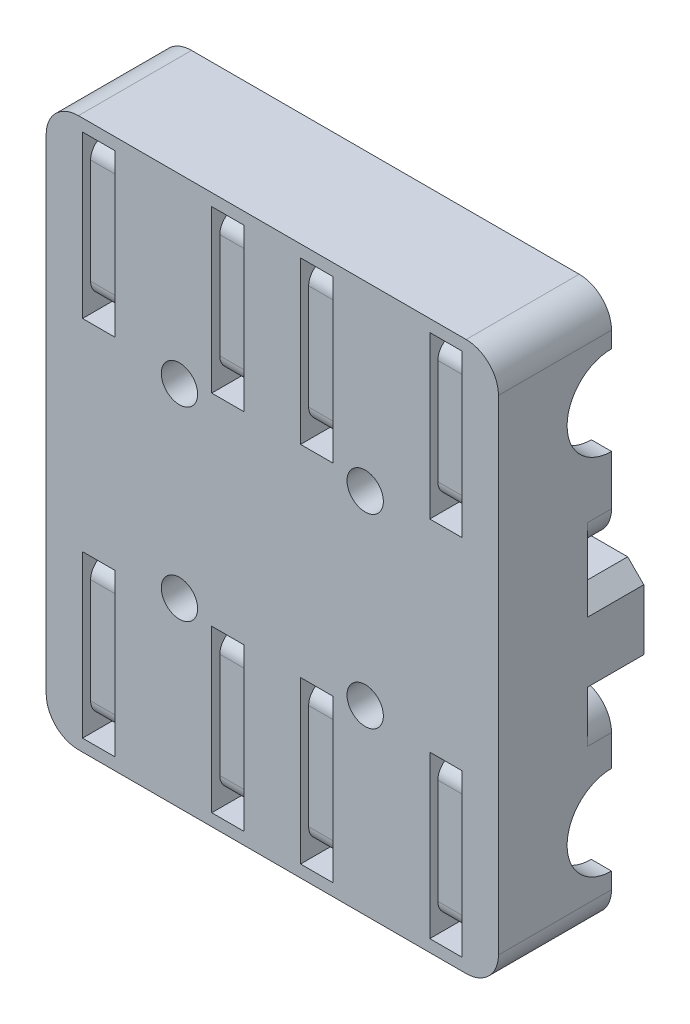
SolidWorks part; units mm, degrees
material "ABS"
ref_plane "Front Plane" through (0, 0, 0) normal (0, 0, 1) x (1, 0, 0)
ref_plane "Top Plane" through (0, 0, 0) normal (0, 1, 0) x (1, 0, 0)
ref_plane "Right Plane" through (0, 0, 0) normal (1, 0, 0) x (0, 0, -1)
sketch "Sketch1" plane through (0, 0, 0) normal (0, 0, 1) x (1, 0, 0)
  line L1 (0, 0) -> (56, 0)
  line L2 (0, 0) -> (0, 68)
  line L3 (0, 68) -> (56, 68)
  line L4 (56, 0) -> (56, 68)
  dimension "D1" = 68
  dimension "D2" = 56
extrude "Boss-Extrude1" add sketch "Sketch1" along normal blind 18
sketch "Sketch2" plane through (0, 0, 18) normal (0, 0, 1) x (1, 0, 0)
  line L0 (0, 34) -> (56, 34) construction
  line L1 (4, 68) -> (52, 68)
  line L2 (0, 64) -> (0, 4)
  line L3 (4, 0) -> (52, 0)
  line L4 (56, 64) -> (56, 4)
  line L5 (4.5, 47.25) -> (0, 47.25) construction
  line L6 (4.5, 48) -> (8.5, 48)
  line L7 (39.5, 45.5) -> (16.5, 45.5) construction
  line L8 (28, 45.5) -> (28, 68) construction
  line L9 (4.5, 48) -> (4.5, 46.5)
  line L10 (4.5, 46.5) -> (8.5, 46.5)
  line L11 (8.5, 48) -> (8.5, 46.5)
  line L12 (0, 68) -> (0, 0) construction
  line L13 (8.5, 47.25) -> (20.5, 47.25) construction
  line L14 (24.5, 47.25) -> (31.5, 47.25) construction
  line L15 (20.5, 48) -> (24.5, 48)
  line L16 (20.5, 48) -> (20.5, 46.5)
  line L17 (20.5, 46.5) -> (24.5, 46.5)
  line L18 (24.5, 48) -> (24.5, 46.5)
  line L19 (35.5, 47.25) -> (47.5, 47.25) construction
  line L20 (31.5, 48) -> (35.5, 48)
  line L21 (31.5, 48) -> (31.5, 46.5)
  line L22 (31.5, 46.5) -> (35.5, 46.5)
  line L23 (35.5, 48) -> (35.5, 46.5)
  line L24 (51.5, 47.25) -> (56, 47.25) construction
  line L25 (47.5, 48) -> (51.5, 48)
  line L26 (47.5, 48) -> (47.5, 46.5)
  line L27 (47.5, 46.5) -> (51.5, 46.5)
  line L28 (51.5, 48) -> (51.5, 46.5)
  line L29 (0, 56.5) -> (56, 56.5) construction
  line L30 (47.5, 65) -> (51.5, 65)
  line L31 (51.5, 65) -> (51.5, 66.5)
  line L32 (47.5, 66.5) -> (51.5, 66.5)
  line L33 (47.5, 65) -> (47.5, 66.5)
  line L34 (35.5, 65) -> (35.5, 66.5)
  line L35 (31.5, 65) -> (35.5, 65)
  line L36 (31.5, 66.5) -> (35.5, 66.5)
  line L37 (31.5, 65) -> (31.5, 66.5)
  line L38 (20.5, 65) -> (24.5, 65)
  line L39 (20.5, 65) -> (20.5, 66.5)
  line L40 (24.5, 65) -> (24.5, 66.5)
  line L41 (20.5, 66.5) -> (24.5, 66.5)
  line L42 (8.5, 65) -> (8.5, 66.5)
  line L43 (4.5, 65) -> (8.5, 65)
  line L44 (4.5, 66.5) -> (8.5, 66.5)
  line L45 (4.5, 65) -> (4.5, 66.5)
  line L46 (8.5, 20) -> (8.5, 21.5)
  line L47 (4.5, 21.5) -> (8.5, 21.5)
  line L48 (4.5, 20) -> (4.5, 21.5)
  line L49 (4.5, 20) -> (8.5, 20)
  line L50 (24.5, 20) -> (24.5, 21.5)
  line L51 (20.5, 21.5) -> (24.5, 21.5)
  line L52 (20.5, 20) -> (20.5, 21.5)
  line L53 (20.5, 20) -> (24.5, 20)
  line L54 (35.5, 20) -> (35.5, 21.5)
  line L55 (31.5, 21.5) -> (35.5, 21.5)
  line L56 (31.5, 20) -> (31.5, 21.5)
  line L57 (31.5, 20) -> (35.5, 20)
  line L58 (51.5, 20) -> (51.5, 21.5)
  line L59 (47.5, 21.5) -> (51.5, 21.5)
  line L60 (47.5, 20) -> (47.5, 21.5)
  line L61 (47.5, 20) -> (51.5, 20)
  line L62 (47.5, 3) -> (47.5, 1.5)
  line L63 (47.5, 1.5) -> (51.5, 1.5)
  line L64 (51.5, 3) -> (51.5, 1.5)
  line L65 (47.5, 3) -> (51.5, 3)
  line L66 (31.5, 3) -> (31.5, 1.5)
  line L67 (31.5, 1.5) -> (35.5, 1.5)
  line L68 (31.5, 3) -> (35.5, 3)
  line L69 (35.5, 3) -> (35.5, 1.5)
  line L70 (20.5, 1.5) -> (24.5, 1.5)
  line L71 (24.5, 3) -> (24.5, 1.5)
  line L72 (20.5, 3) -> (20.5, 1.5)
  line L73 (20.5, 3) -> (24.5, 3)
  line L74 (4.5, 3) -> (4.5, 1.5)
  line L75 (4.5, 1.5) -> (8.5, 1.5)
  line L76 (4.5, 3) -> (8.5, 3)
  line L77 (8.5, 3) -> (8.5, 1.5)
  line L78 (16.5, 45.5) -> (16.5, 22.5) construction
  line L79 (39.5, 45.5) -> (39.5, 22.5) construction
  arc A0 (56, 4) -> (52, 0) centre (52, 4) cw
  arc A1 (4, 0) -> (0, 4) centre (4, 4) cw
  arc A2 (56, 64) -> (52, 68) centre (52, 64) ccw
  arc A3 (4, 68) -> (0, 64) centre (4, 64) ccw
  circle A4 centre (16.5, 22.5) radius 2.25
  circle A5 centre (16.5, 45.5) radius 2.25
  circle A6 centre (39.5, 45.5) radius 2.25
  circle A7 centre (39.5, 22.5) radius 2.25
  point P8 (56, 0)
  point P15 (0, 68)
  point P106 (39.5, 22.5)
  point P107 (39.5, 19.4757)
  point P108 (16.5, 22.5)
  point P109 (16.5, 22)
  line M29 (0, 68) -> (0, 0)
  line M30 (0, 0) -> (56, 0)
  line M31 (56, 0) -> (56, 68)
  line M32 (56, 68) -> (0, 68)
  dimension "D1" = 4
  dimension "D2" = 4.5
  dimension "D3" = 23
  dimension "D4" = 22.5
  dimension "D5" = 1.5
  dimension "D6" = 4
  dimension "D7" = 4.5
  dimension "D8" = 12
  dimension "D9" = 20.75
  dimension "D10" = 9.25
  dimension "D11" = 23
  dimension "D12" = 23
extrude "Cut-Extrude1" cut sketch "Sketch2" against normal through all contours L45 L43 L42 L44 | L41 L39 L38 L40 | L37 L35 L34 L36 | L28 L25 L26 L27 | A6 | L23 L20 L21 L22 | L18 L15 L16 L17 | A5 | L11 L6 L9 L10 | L48 L49 L46 L47 | A4 | L52 L53 L50 L51 | A7 | L73 L72 L70 L71 | A1 M30 M29 | A0 M31 M30 | A3 M32 M29 | A2 M31 M32 | L30 L31 L32 L33 | L57 L54 L55 L56 | L59 L58 L61 L60 | L65 L64 L63 L62 | L67 L69 L68 L66 | L75 L77 L76 L74
sketch "Sketch3" plane through (0, 0, 18) normal (0, 0, 1) x (1, 0, 0)
  line L0 (56, 34) -> (0, 34) construction
  line L1 (4.5, 65) -> (8.5, 65)
  line L2 (4.5, 65) -> (4.5, 48)
  line L3 (4.5, 48) -> (8.5, 48)
  line L4 (8.5, 65) -> (8.5, 48)
  line L5 (20.5, 65) -> (24.5, 65)
  line L6 (20.5, 65) -> (20.5, 48)
  line L7 (20.5, 48) -> (24.5, 48)
  line L8 (24.5, 65) -> (24.5, 48)
  line L9 (31.5, 65) -> (35.5, 65)
  line L10 (31.5, 65) -> (31.5, 48)
  line L11 (31.5, 48) -> (35.5, 48)
  line L12 (35.5, 65) -> (35.5, 48)
  line L13 (47.5, 65) -> (51.5, 65)
  line L14 (47.5, 65) -> (47.5, 48)
  line L15 (47.5, 48) -> (51.5, 48)
  line L16 (51.5, 65) -> (51.5, 48)
  line L17 (56, 4) -> (56, 64) construction
  line L18 (0, 64) -> (0, 4) construction
  line L19 (51.5, 3) -> (51.5, 20)
  line L20 (47.5, 20) -> (51.5, 20)
  line L21 (47.5, 3) -> (47.5, 20)
  line L22 (47.5, 3) -> (51.5, 3)
  line L23 (35.5, 3) -> (35.5, 20)
  line L24 (31.5, 20) -> (35.5, 20)
  line L25 (31.5, 3) -> (31.5, 20)
  line L26 (31.5, 3) -> (35.5, 3)
  line L27 (24.5, 3) -> (24.5, 20)
  line L28 (20.5, 20) -> (24.5, 20)
  line L29 (20.5, 3) -> (20.5, 20)
  line L30 (20.5, 3) -> (24.5, 3)
  line L31 (8.5, 3) -> (8.5, 20)
  line L32 (4.5, 20) -> (8.5, 20)
  line L33 (4.5, 3) -> (4.5, 20)
  line L34 (4.5, 3) -> (8.5, 3)
extrude "Cut-Extrude2" cut sketch "Sketch3" against normal blind 1
ref_plane "Plane2" through (53.5, 0, 0) normal (1, 0, 0) x (0, 0, -1)
sketch "Sketch5" plane through (53.5, 0, 0) normal (1, 0, 0) x (0, 0, -1)
  line L1 (0, 0) -> (-18, 0) construction
  line L2 (0, 4) -> (0, 64) construction
  circle A0 centre (-4, 11.5) radius 7.5
  point P2 (-1.2356, 11.5)
  point P6 (0, 0)
  dimension "D1" = 15
  dimension "D2" = 11.5
  dimension "D3" = 4
extrude "Cut-Extrude3" cut sketch "Sketch5" against normal blind 24.5 contours A0
ref_plane "Plane3" through (28, 0, 0) normal (1, 0, 0) x (0, 0, -1)
ref_plane "Plane4" through (0, 34, 0) normal (0, -1, 0) x (-1, 0, 0)
mirror "Mirror1" about plane through (28, 0, 0) normal (1, 0, 0) of "Cut-Extrude3"
sketch "Sketch7" plane through (56, 0, 0) normal (1, 0, 0) x (0, 0, -1)
  line L1 (0, 0) -> (-18, 0) construction
  line L2 (0, 4) -> (0, 64) construction
  circle A0 centre (-4, 11.5) radius 5.5
  point P2 (-1.5987, 11.5)
  point P6 (0, 0)
  dimension "D1" = 11
  dimension "D2" = 11.5
  dimension "D3" = 4
extrude "Cut-Extrude4" cut sketch "Sketch7" against normal through all
mirror "Mirror3" about plane through (0, 34, 0) normal (0, -1, 0) of "Cut-Extrude3", "Mirror1", "Cut-Extrude4"
fillet "Fillet1" radius 2 16 edges at (49.5, 3, 17) (33.5, 3, 17) (22.5, 3, 17) (6.5, 3, 17) (6.5, 20, 17) (22.5, 20, 17) (33.5, 20, 17) (49.5, 20, 17) (6.5, 48, 17) (6.5, 65, 17) (22.5, 65, 17) (22.5, 48, 17) (33.5, 48, 17) (33.5, 65, 17) (49.5, 65, 17) (49.5, 48, 17)
sketch "Sketch9" plane through (0, 0, 0) normal (0, 0, -1) x (-1, 0, 0)
  line L0 (-54.91, 27.45) -> (-54.01, 27.45) construction
  line L1 (-52.4311, 27.702) -> (-52.2422, 27.3355)
  line L2 (-53.5978, 27.3355) -> (-53.4089, 27.702)
  line L3 (-54.4211, 27.702) -> (-54.2322, 27.3355)
  line L4 (-54.01, 27.2) -> (-53.82, 27.2)
  line L5 (-55.5878, 27.3355) -> (-55.3989, 27.702)
  line L6 (-54.91, 27.45) -> (-55.81, 27.45) construction
  line L7 (-55.81, 27.2) -> (-56, 27.2)
  line L8 (-50.4411, 27.702) -> (-50.2522, 27.3355)
  line L9 (-29, 17.8443) -> (-53.5, 17.8443) construction
  line L10 (-56, 15.2749) -> (-56, 52.7251) construction
  line L12 (-51.6078, 27.3355) -> (-51.4189, 27.702)
  line L13 (-51.83, 27.2) -> (-52.02, 27.2)
  line L14 (-48.4511, 27.702) -> (-48.2622, 27.3355)
  line L15 (-49.6178, 27.3355) -> (-49.4289, 27.702)
  line L16 (-49.84, 27.2) -> (-50.03, 27.2)
  line L17 (-46.4611, 27.702) -> (-46.2722, 27.3355)
  line L18 (-47.6278, 27.3355) -> (-47.4389, 27.702)
  line L19 (-47.85, 27.2) -> (-48.04, 27.2)
  line L20 (-44.4711, 27.702) -> (-44.2822, 27.3355)
  line L21 (-45.6378, 27.3355) -> (-45.4489, 27.702)
  line L22 (-45.86, 27.2) -> (-46.05, 27.2)
  line L23 (-42.4811, 27.702) -> (-42.2922, 27.3355)
  line L24 (-43.6478, 27.3355) -> (-43.4589, 27.702)
  line L25 (-43.87, 27.2) -> (-44.06, 27.2)
  line L26 (-40.4911, 27.702) -> (-40.3022, 27.3355)
  line L27 (-41.6578, 27.3355) -> (-41.4689, 27.702)
  line L28 (-41.88, 27.2) -> (-42.07, 27.2)
  line L29 (-38.5011, 27.702) -> (-38.3122, 27.3355)
  line L30 (-39.6678, 27.3355) -> (-39.4789, 27.702)
  line L31 (-39.89, 27.2) -> (-40.08, 27.2)
  line L32 (-36.5111, 27.702) -> (-36.3222, 27.3355)
  line L33 (-37.6778, 27.3355) -> (-37.4889, 27.702)
  line L34 (-37.9, 27.2) -> (-38.09, 27.2)
  line L35 (-34.5211, 27.702) -> (-34.3322, 27.3355)
  line L36 (-35.6878, 27.3355) -> (-35.4989, 27.702)
  line L37 (-35.91, 27.2) -> (-36.1, 27.2)
  line L38 (-34.11, 27.2) -> (-34.11, 34.7)
  line L39 (-36.11, 36.7) -> (-54, 36.7)
  line L40 (-56, 34.7) -> (-56, 27.2)
  line L41 (-54, 36.7) -> (-56, 34.7)
  line L42 (-34.11, 34.7) -> (-36.11, 36.7)
  line L43 (-52, 24.8443) -> (-4, 24.8443)
  line L44 (-1.09, 27.45) -> (-0.19, 27.45) construction
  line L45 (-52, 40.8443) -> (-4, 40.8443)
  line L46 (-1.09, 27.45) -> (-1.99, 27.45) construction
  line L47 (-48.94, 26.8443) -> (-48.94, 24.8443) construction
  line L48 (-56, 44.8443) -> (-56, 20.8443)
  line L49 (-28, 40.8443) -> (-28, 24.8443) construction
  line L50 (0, 44.8443) -> (0, 20.8443)
  line L51 (-21.89, 34.7) -> (-19.89, 36.7)
  line L52 (-2, 36.7) -> (0, 34.7)
  line L53 (0, 34.7) -> (0, 27.2)
  line L54 (-19.89, 36.7) -> (-2, 36.7)
  line L55 (-21.89, 27.2) -> (-21.89, 34.7)
  line L56 (-20.09, 27.2) -> (-19.9, 27.2)
  line L57 (-20.3122, 27.3355) -> (-20.5011, 27.702)
  line L58 (-21.4789, 27.702) -> (-21.6678, 27.3355)
  line L59 (-18.1, 27.2) -> (-17.91, 27.2)
  line L60 (-18.3222, 27.3355) -> (-18.5111, 27.702)
  line L61 (-19.4889, 27.702) -> (-19.6778, 27.3355)
  line L62 (-16.11, 27.2) -> (-15.92, 27.2)
  line L63 (-16.3322, 27.3355) -> (-16.5211, 27.702)
  line L64 (-17.4989, 27.702) -> (-17.6878, 27.3355)
  line L65 (-14.12, 27.2) -> (-13.93, 27.2)
  line L66 (-14.3422, 27.3355) -> (-14.5311, 27.702)
  line L67 (-15.5089, 27.702) -> (-15.6978, 27.3355)
  line L68 (-12.13, 27.2) -> (-11.94, 27.2)
  line L69 (-12.3522, 27.3355) -> (-12.5411, 27.702)
  line L70 (-13.5189, 27.702) -> (-13.7078, 27.3355)
  line L71 (-10.14, 27.2) -> (-9.95, 27.2)
  line L72 (-10.3622, 27.3355) -> (-10.5511, 27.702)
  line L73 (-11.5289, 27.702) -> (-11.7178, 27.3355)
  line L74 (-8.15, 27.2) -> (-7.96, 27.2)
  line L75 (-8.3722, 27.3355) -> (-8.5611, 27.702)
  line L76 (-9.5389, 27.702) -> (-9.7278, 27.3355)
  line L77 (-6.16, 27.2) -> (-5.97, 27.2)
  line L78 (-6.3822, 27.3355) -> (-6.5711, 27.702)
  line L79 (-7.5489, 27.702) -> (-7.7378, 27.3355)
  line L80 (-4.17, 27.2) -> (-3.98, 27.2)
  line L81 (-4.3922, 27.3355) -> (-4.5811, 27.702)
  line L82 (-5.5589, 27.702) -> (-5.7478, 27.3355)
  line L83 (-0.19, 27.2) -> (0, 27.2)
  line L84 (-0.4122, 27.3355) -> (-0.6011, 27.702)
  line L85 (-1.99, 27.2) -> (-2.18, 27.2)
  line L86 (-1.5789, 27.702) -> (-1.7678, 27.3355)
  line L87 (-2.4022, 27.3355) -> (-2.5911, 27.702)
  line L88 (-3.5689, 27.702) -> (-3.7578, 27.3355)
  arc A0 (-54.4211, 27.702) -> (-55.3989, 27.702) centre (-54.91, 27.45) ccw
  arc A1 (-54.2322, 27.3355) -> (-54.01, 27.2) centre (-54.01, 27.45) ccw
  arc A2 (-55.81, 27.2) -> (-55.5878, 27.3355) centre (-55.81, 27.45) ccw
  arc A3 (-52.2422, 27.3355) -> (-52.02, 27.2) centre (-52.02, 27.45) ccw
  arc A4 (-52.4311, 27.702) -> (-53.4089, 27.702) centre (-52.92, 27.45) ccw
  arc A5 (-53.82, 27.2) -> (-53.5978, 27.3355) centre (-53.82, 27.45) ccw
  arc A6 (-50.2522, 27.3355) -> (-50.03, 27.2) centre (-50.03, 27.45) ccw
  arc A7 (-50.4411, 27.702) -> (-51.4189, 27.702) centre (-50.93, 27.45) ccw
  arc A8 (-51.83, 27.2) -> (-51.6078, 27.3355) centre (-51.83, 27.45) ccw
  arc A9 (-48.2622, 27.3355) -> (-48.04, 27.2) centre (-48.04, 27.45) ccw
  arc A10 (-48.4511, 27.702) -> (-49.4289, 27.702) centre (-48.94, 27.4125) ccw
  arc A11 (-49.84, 27.2) -> (-49.6178, 27.3355) centre (-49.84, 27.45) ccw
  arc A12 (-46.2722, 27.3355) -> (-46.05, 27.2) centre (-46.05, 27.45) ccw
  arc A13 (-46.4611, 27.702) -> (-47.4389, 27.702) centre (-46.95, 27.45) ccw
  arc A14 (-47.85, 27.2) -> (-47.6278, 27.3355) centre (-47.85, 27.45) ccw
  arc A15 (-44.2822, 27.3355) -> (-44.06, 27.2) centre (-44.06, 27.45) ccw
  arc A16 (-44.4711, 27.702) -> (-45.4489, 27.702) centre (-44.96, 27.45) ccw
  arc A17 (-45.86, 27.2) -> (-45.6378, 27.3355) centre (-45.86, 27.45) ccw
  arc A18 (-42.2922, 27.3355) -> (-42.07, 27.2) centre (-42.07, 27.45) ccw
  arc A19 (-42.4811, 27.702) -> (-43.4589, 27.702) centre (-42.97, 27.45) ccw
  arc A20 (-43.87, 27.2) -> (-43.6478, 27.3355) centre (-43.87, 27.45) ccw
  arc A21 (-40.3022, 27.3355) -> (-40.08, 27.2) centre (-40.08, 27.45) ccw
  arc A22 (-40.4911, 27.702) -> (-41.4689, 27.702) centre (-40.98, 27.45) ccw
  arc A23 (-41.88, 27.2) -> (-41.6578, 27.3355) centre (-41.88, 27.45) ccw
  arc A24 (-38.3122, 27.3355) -> (-38.09, 27.2) centre (-38.09, 27.45) ccw
  arc A25 (-38.5011, 27.702) -> (-39.4789, 27.702) centre (-38.99, 27.45) ccw
  arc A26 (-39.89, 27.2) -> (-39.6678, 27.3355) centre (-39.89, 27.45) ccw
  arc A27 (-36.3222, 27.3355) -> (-36.1, 27.2) centre (-36.1, 27.45) ccw
  arc A28 (-36.5111, 27.702) -> (-37.4889, 27.702) centre (-37, 27.45) ccw
  arc A29 (-37.9, 27.2) -> (-37.6778, 27.3355) centre (-37.9, 27.45) ccw
  arc A30 (-34.3322, 27.3355) -> (-34.11, 27.2) centre (-34.11, 27.45) ccw
  arc A31 (-34.5211, 27.702) -> (-35.4989, 27.702) centre (-35.01, 27.45) ccw
  arc A32 (-35.91, 27.2) -> (-35.6878, 27.3355) centre (-35.91, 27.45) ccw
  arc A33 (-52, 24.8443) -> (-56, 20.8443) centre (-52, 20.8443) ccw
  arc A34 (-56, 44.8443) -> (-52, 40.8443) centre (-52, 44.8443) ccw
  arc A35 (0, 44.8443) -> (-4, 40.8443) centre (-4, 44.8443) cw
  arc A36 (-4, 24.8443) -> (0, 20.8443) centre (-4, 20.8443) cw
  arc A37 (-20.09, 27.2) -> (-20.3122, 27.3355) centre (-20.09, 27.45) cw
  arc A38 (-21.4789, 27.702) -> (-20.5011, 27.702) centre (-20.99, 27.45) cw
  arc A39 (-21.6678, 27.3355) -> (-21.89, 27.2) centre (-21.89, 27.45) cw
  arc A40 (-18.1, 27.2) -> (-18.3222, 27.3355) centre (-18.1, 27.45) cw
  arc A41 (-19.4889, 27.702) -> (-18.5111, 27.702) centre (-19, 27.45) cw
  arc A42 (-19.6778, 27.3355) -> (-19.9, 27.2) centre (-19.9, 27.45) cw
  arc A43 (-16.11, 27.2) -> (-16.3322, 27.3355) centre (-16.11, 27.45) cw
  arc A44 (-17.4989, 27.702) -> (-16.5211, 27.702) centre (-17.01, 27.45) cw
  arc A45 (-17.6878, 27.3355) -> (-17.91, 27.2) centre (-17.91, 27.45) cw
  arc A46 (-14.12, 27.2) -> (-14.3422, 27.3355) centre (-14.12, 27.45) cw
  arc A47 (-15.5089, 27.702) -> (-14.5311, 27.702) centre (-15.02, 27.45) cw
  arc A48 (-15.6978, 27.3355) -> (-15.92, 27.2) centre (-15.92, 27.45) cw
  arc A49 (-12.13, 27.2) -> (-12.3522, 27.3355) centre (-12.13, 27.45) cw
  arc A50 (-13.5189, 27.702) -> (-12.5411, 27.702) centre (-13.03, 27.45) cw
  arc A51 (-13.7078, 27.3355) -> (-13.93, 27.2) centre (-13.93, 27.45) cw
  arc A52 (-10.14, 27.2) -> (-10.3622, 27.3355) centre (-10.14, 27.45) cw
  arc A53 (-11.5289, 27.702) -> (-10.5511, 27.702) centre (-11.04, 27.45) cw
  arc A54 (-11.7178, 27.3355) -> (-11.94, 27.2) centre (-11.94, 27.45) cw
  arc A55 (-8.15, 27.2) -> (-8.3722, 27.3355) centre (-8.15, 27.45) cw
  arc A56 (-9.5389, 27.702) -> (-8.5611, 27.702) centre (-9.05, 27.45) cw
  arc A57 (-9.7278, 27.3355) -> (-9.95, 27.2) centre (-9.95, 27.45) cw
  arc A58 (-6.16, 27.2) -> (-6.3822, 27.3355) centre (-6.16, 27.45) cw
  arc A59 (-7.5489, 27.702) -> (-6.5711, 27.702) centre (-7.06, 27.4125) cw
  arc A60 (-7.7378, 27.3355) -> (-7.96, 27.2) centre (-7.96, 27.45) cw
  arc A61 (-4.17, 27.2) -> (-4.3922, 27.3355) centre (-4.17, 27.45) cw
  arc A62 (-5.5589, 27.702) -> (-4.5811, 27.702) centre (-5.07, 27.45) cw
  arc A63 (-5.7478, 27.3355) -> (-5.97, 27.2) centre (-5.97, 27.45) cw
  arc A64 (-2.18, 27.2) -> (-2.4022, 27.3355) centre (-2.18, 27.45) cw
  arc A65 (-3.5689, 27.702) -> (-2.5911, 27.702) centre (-3.08, 27.45) cw
  arc A66 (-3.7578, 27.3355) -> (-3.98, 27.2) centre (-3.98, 27.45) cw
  arc A67 (-0.19, 27.2) -> (-0.4122, 27.3355) centre (-0.19, 27.45) cw
  arc A68 (-1.7678, 27.3355) -> (-1.99, 27.2) centre (-1.99, 27.45) cw
  arc A69 (-1.5789, 27.702) -> (-0.6011, 27.702) centre (-1.09, 27.45) cw
  point P5 (-56, 36.7)
  point P120 (-34.11, 36.7)
  point P127 (-41.25, 17.8443)
  dimension "D1" = 1.1
  dimension "D2" = 0.5
  dimension "D5" = 0.19
  dimension "D13" = 8
  dimension "D4" = 0.19
  dimension "D7" = 2
  dimension "D8" = 9.5
  dimension "D9" = 2
  dimension "D10" = 45
  dimension "D11" = 2
  dimension "D12" = 45
  dimension "D14" = 24
  dimension "D15" = 16
  dimension "D16" = 7
extrude "Cut-Extrude6" cut sketch "Sketch9" against normal blind 7 contours A69 L86 A68 L85 A64 L87 A65 L88 A66 L80 A61 L81 A62 L82 A63 L77 A58 L78 A59 L79 A60 L74 A55 L75 A56 L76 A57 L71 A52 L72 A53 L73 A54 L68 A49 L69 A50 L70 A51 L65 A46 L66 A47 L67 A48 L62 A43 L63 A44 L64 A45
sketch "Sketch10" plane through (0, 0, 0) normal (-1, 0, 0) x (0, 0, 1)
  line L2 (0, 0) -> (4, 0)
  line L3 (0, 0) -> (0, 24.8443)
  line L4 (0, 24.8443) -> (4, 24.8443)
  line L5 (4, 0) -> (4, 24.8443)
  line L6 (7, 24.8443) -> (0, 24.8443) construction
  line L7 (7, 40.8443) -> (0, 40.8443) construction
  line L8 (0, 68) -> (4, 68)
  line L9 (0, 68) -> (0, 40.8443)
  line L10 (0, 40.8443) -> (4, 40.8443)
  line L11 (4, 68) -> (4, 40.8443)
  dimension "D1" = 4
  dimension "D2" = 4
extrude "Cut-Extrude7" cut sketch "Sketch10" against normal through all
